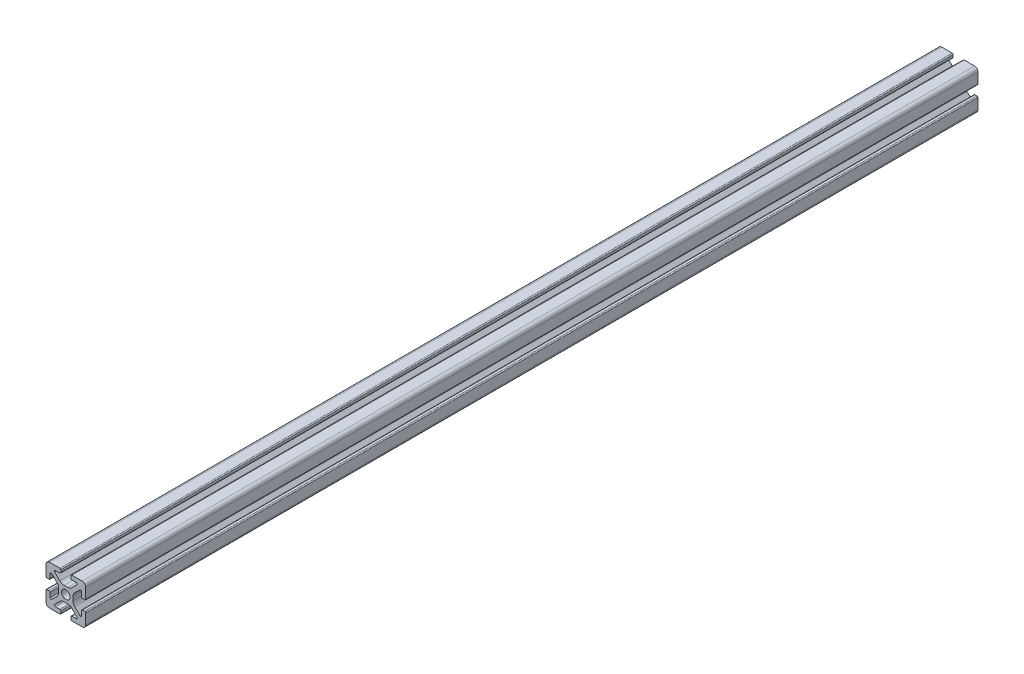
SolidWorks part; units mm, degrees
material "6063-T6"
ref_plane "Front Plane" through (0, 0, 0) normal (0, 0, 1) x (1, 0, 0)
ref_plane "Top Plane" through (0, 0, 0) normal (0, 1, 0) x (1, 0, 0)
ref_plane "Right Plane" through (0, 0, 0) normal (1, 0, 0) x (0, 0, -1)
sketch "Sketch2" plane through (0, 0, 0) normal (0, 0, 1) x (1, 0, 0)
  line L0 (0, 10) -> (0, -10) construction
  line L1 (-10, 0) -> (10, 0) construction
  line L2 (2.5, -10) -> (10, -10)
  line L3 (10, -10) -> (10, -2.5)
  line L4 (2.5, -10) -> (2.5, -7.9246)
  line L5 (2.5, -7.9246) -> (6.4571, -7.9246)
  line L6 (6.4571, -7.9246) -> (2.1325, -3.6)
  line L7 (0, 0) -> (10, -10) construction
  line L8 (10, -2.5) -> (7.9246, -2.5)
  line L9 (7.9246, -2.5) -> (7.9246, -6.4571)
  line L10 (7.9246, -6.4571) -> (3.6, -2.1325)
  line L11 (5.7623, -4.2948) -> (4.2948, -5.7623) construction
  circle A0 centre (0, 0) radius 2.15
  arc A1 (5.25, -7.9246) -> (5.6036, -7.0711) centre (5.25, -7.4246) ccw construction
  point P8 (0, -3.6)
  point P16 (5.0286, -5.0286)
  dimension "Center Hole Diameter" = 4.3
  dimension "D3" = 0.5
  dimension "Rail Height" = 20
  dimension "Rail Width" = 20
  dimension "T-Slot Width" = 5
  dimension "Slot Depth" = 6.4
  dimension "Slot Inner Width" = 11.5
sketch "Sketch3" plane through (0, 0, 0) normal (1, 0, 0) x (0, 0, -1)
  line L0 (-225, -10) -> (225, -10) construction
  line L1 (-199.6, 0) -> (199.6, 0) construction
  line L2 (0, 10) -> (0, -10) construction
  line L3 (0, 10) -> (0, -10) construction
  point P6 (-199.6, 0)
  point P8 (199.6, 0)
  dimension "Length" = 450
  dimension "D1" = 25.4
sketch "Sketch4" plane through (0, 0, 0) normal (0, 0, 1) x (1, 0, 0)
  line L0 (3, -10) -> (8.25, -10)
  line L1 (2.5, -10) -> (10, -10) construction
  line L2 (2.5, -10) -> (2.5, -7.9246) construction
  line L3 (2.5, -7.9246) -> (6.4571, -7.9246) construction
  line L4 (2.5, -8.4246) -> (2.5, -9.5)
  line L5 (3, -7.9246) -> (5.25, -7.9246)
  line L6 (0, -3.6) -> (0.8898, -3.6)
  line L7 (6.4571, -7.9246) -> (2.1325, -3.6) construction
  line L8 (3.0112, -4.4787) -> (5.6036, -7.0711)
  line L9 (10, -10) -> (10, -2.5) construction
  line L10 (7.9246, -6.4571) -> (3.6, -2.1325) construction
  line L11 (7.9246, -2.5) -> (7.9246, -6.4571) construction
  line L12 (7.9246, -5.25) -> (7.9246, -3)
  line L13 (10, -2.5) -> (7.9246, -2.5) construction
  line L14 (8.4246, -2.5) -> (9.5, -2.5)
  line L15 (10, -3) -> (10, -8.25)
  line L16 (7.0711, -5.6036) -> (4.4787, -3.0112)
  line L17 (3.6, 0) -> (3.6, -0.8898)
  line L18 (-10, 0) -> (10, 0) construction
  line L19 (0, -3.6) -> (0, -2.15)
  line L20 (0, 10) -> (0, -10) construction
  line L21 (3.6, 0) -> (2.15, 0)
  arc A0 (2.5, -9.5) -> (3, -10) centre (3, -9.5) ccw
  arc A1 (5.25, -7.9246) -> (5.6036, -7.0711) centre (5.25, -7.4246) ccw construction
  arc A2 (2.5, -8.4246) -> (3, -7.9246) centre (3, -8.4246) cw
  arc A3 (5.25, -7.9246) -> (5.6036, -7.0711) centre (5.25, -7.4246) ccw
  arc A4 (0.8898, -3.6) -> (3.0112, -4.4787) centre (0.8898, -6.6) cw
  arc A5 (8.25, -10) -> (10, -8.25) centre (8.25, -8.25) ccw
  arc A6 (7.0711, -5.6036) -> (7.9246, -5.25) centre (7.4246, -5.25) ccw
  arc A7 (7.9246, -3) -> (8.4246, -2.5) centre (8.4246, -3) cw
  arc A8 (9.5, -2.5) -> (10, -3) centre (9.5, -3) cw
  arc A9 (4.4787, -3.0112) -> (3.6, -0.8898) centre (6.6, -0.8898) cw
  circle A10 centre (0, 0) radius 2.15 construction
  arc A11 (0, -2.15) -> (2.15, 0) centre (0, 0) ccw
  dimension "D1" = 1.75
  dimension "D2" = 3
extrude "Boss-Extrude1" add sketch "Sketch4" along normal mid plane 450
mirror "Mirror1" about plane through (0, 0, 0) normal (1, 0, 0) of bodies 134
mirror "Mirror2" about plane through (0, 0, 0) normal (0, 1, 0) of bodies 135
equation "\"D3@Sketch2\"=\"T-Slot Width@Sketch2\"*0.1"
equation "\"D1@Sketch4\"=\"D3@Sketch2\"*3.5"
equation "\"D2@Sketch4\"=\"D3@Sketch2\"*6"
equation "\"D1@Boss-Extrude1\"=\"Length@Sketch3\""
